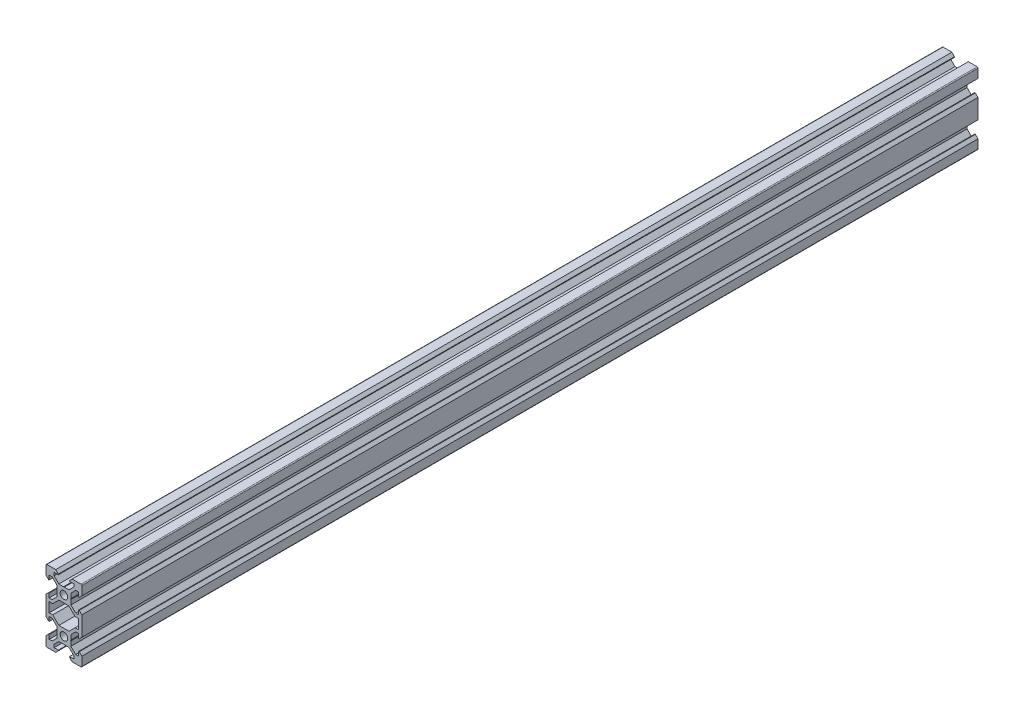
SolidWorks part; units mm, degrees
material "6061-T6 (SS)"
ref_plane "Front Plane" through (0, 0, 0) normal (0, 0, 1) x (1, 0, 0)
ref_plane "Top Plane" through (0, 0, 0) normal (0, 1, 0) x (1, 0, 0)
ref_plane "Right Plane" through (0, 0, 0) normal (1, 0, 0) x (0, 0, -1)
sketch "Sketch1" plane through (0, 0, 0) normal (0, 0, 1) x (1, 0, 0)
  line L0 (0, 0) -> (10, 0) construction
  line L1 (9.5, -20) -> (-9.5, -20)
  line L2 (10, -19.5) -> (10, 19.5)
  line L3 (9.5, 20) -> (-9.5, 20)
  line L4 (-10, -19.5) -> (-10, 19.5)
  line L5 (10, -20) -> (-10, 20) construction
  line L6 (10, 20) -> (-10, -20) construction
  circle A0 centre (0, 10) radius 2.1
  circle A1 centre (0, -10) radius 2.1
  arc A2 (-9.5, -20) -> (-10, -19.5) centre (-9.5, -19.5) cw
  arc A3 (9.5, -20) -> (10, -19.5) centre (9.5, -19.5) ccw
  arc A4 (10, 19.5) -> (9.5, 20) centre (9.5, 19.5) ccw
  arc A5 (-9.5, 20) -> (-10, 19.5) centre (-9.5, 19.5) ccw
  point P0 (0, 0)
  line B0 (0, 10) -> (0, 20) construction
  line B1 (0, 13.69) -> (-0.21, 13.9)
  line B2 (-0.21, 13.9) -> (-2.8393, 13.9)
  line B3 (-2.8393, 13.9) -> (-5.5, 16.5607)
  line B4 (-5.5, 16.5607) -> (-5.5, 18.2)
  line B5 (-5.5, 18.2) -> (-3.125, 18.2)
  line B6 (-3.125, 18.2) -> (-3.125, 18.545)
  line B7 (-3.125, 18.545) -> (-4.58, 20)
  line B8 (-4.58, 20) -> (4.58, 20)
  line B9 (0, 10) -> (-5.9132, 15.9132) construction
  line B10 (3.125, 18.545) -> (4.58, 20)
  line B11 (3.125, 18.2) -> (3.125, 18.545)
  line B12 (5.5, 18.2) -> (3.125, 18.2)
  line B13 (5.5, 16.5607) -> (5.5, 18.2)
  line B14 (2.8393, 13.9) -> (5.5, 16.5607)
  line B15 (0.21, 13.9) -> (2.8393, 13.9)
  line B16 (0, 13.69) -> (0.21, 13.9)
  line B17 (0, 10) -> (-10, 10) construction
  line B18 (-3.69, 10) -> (-3.9, 9.79)
  line B19 (-3.9, 9.79) -> (-3.9, 7.1607)
  line B20 (-3.9, 7.1607) -> (-6.5607, 4.5)
  line B21 (-6.5607, 4.5) -> (-8.2, 4.5)
  line B22 (-8.2, 4.5) -> (-8.2, 6.875)
  line B23 (-8.2, 6.875) -> (-8.545, 6.875)
  line B24 (-8.545, 6.875) -> (-10, 5.42)
  line B25 (-10, 5.42) -> (-10, 14.58)
  line B26 (0, 10) -> (-5.9132, 4.0868) construction
  line B27 (-8.545, 13.125) -> (-10, 14.58)
  line B28 (-8.2, 13.125) -> (-8.545, 13.125)
  line B29 (-8.2, 15.5) -> (-8.2, 13.125)
  line B30 (-6.5607, 15.5) -> (-8.2, 15.5)
  line B31 (-3.9, 12.8393) -> (-6.5607, 15.5)
  line B32 (-3.9, 10.21) -> (-3.9, 12.8393)
  line B33 (-3.69, 10) -> (-3.9, 10.21)
  line B34 (0, -10) -> (-10, -10) construction
  line B35 (-3.69, -10) -> (-3.9, -10.21)
  line B36 (-3.9, -10.21) -> (-3.9, -12.8393)
  line B37 (-3.9, -12.8393) -> (-6.5607, -15.5)
  line B38 (-6.5607, -15.5) -> (-8.2, -15.5)
  line B39 (-8.2, -15.5) -> (-8.2, -13.125)
  line B40 (-8.2, -13.125) -> (-8.545, -13.125)
  line B41 (-8.545, -13.125) -> (-10, -14.58)
  line B42 (-10, -14.58) -> (-10, -5.42)
  line B43 (0, -10) -> (-5.9132, -15.9132) construction
  line B44 (-8.545, -6.875) -> (-10, -5.42)
  line B45 (-8.2, -6.875) -> (-8.545, -6.875)
  line B46 (-8.2, -4.5) -> (-8.2, -6.875)
  line B47 (-6.5607, -4.5) -> (-8.2, -4.5)
  line B48 (-3.9, -7.1607) -> (-6.5607, -4.5)
  line B49 (-3.9, -9.79) -> (-3.9, -7.1607)
  line B50 (-3.69, -10) -> (-3.9, -9.79)
  line B51 (0, -10) -> (0, -20) construction
  line B52 (0, -13.69) -> (0.21, -13.9)
  line B53 (0.21, -13.9) -> (2.8393, -13.9)
  line B54 (2.8393, -13.9) -> (5.5, -16.5607)
  line B55 (5.5, -16.5607) -> (5.5, -18.2)
  line B56 (5.5, -18.2) -> (3.125, -18.2)
  line B57 (3.125, -18.2) -> (3.125, -18.545)
  line B58 (3.125, -18.545) -> (4.58, -20)
  line B59 (4.58, -20) -> (-4.58, -20)
  line B60 (0, -10) -> (5.9132, -15.9132) construction
  line B61 (-3.125, -18.545) -> (-4.58, -20)
  line B62 (-3.125, -18.2) -> (-3.125, -18.545)
  line B63 (-5.5, -18.2) -> (-3.125, -18.2)
  line B64 (-5.5, -16.5607) -> (-5.5, -18.2)
  line B65 (-2.8393, -13.9) -> (-5.5, -16.5607)
  line B66 (-0.21, -13.9) -> (-2.8393, -13.9)
  line B67 (0, -13.69) -> (-0.21, -13.9)
  line B68 (0, -10) -> (10, -10) construction
  line B69 (3.69, -10) -> (3.9, -9.79)
  line B70 (3.9, -9.79) -> (3.9, -7.1607)
  line B71 (3.9, -7.1607) -> (6.5607, -4.5)
  line B72 (6.5607, -4.5) -> (8.2, -4.5)
  line B73 (8.2, -4.5) -> (8.2, -6.875)
  line B74 (8.2, -6.875) -> (8.545, -6.875)
  line B75 (8.545, -6.875) -> (10, -5.42)
  line B76 (10, -5.42) -> (10, -14.58)
  line B77 (0, -10) -> (5.9132, -4.0868) construction
  line B78 (8.545, -13.125) -> (10, -14.58)
  line B79 (8.2, -13.125) -> (8.545, -13.125)
  line B80 (8.2, -15.5) -> (8.2, -13.125)
  line B81 (6.5607, -15.5) -> (8.2, -15.5)
  line B82 (3.9, -12.8393) -> (6.5607, -15.5)
  line B83 (3.9, -10.21) -> (3.9, -12.8393)
  line B84 (3.69, -10) -> (3.9, -10.21)
  line B85 (0, 10) -> (10, 10) construction
  line B86 (3.69, 10) -> (3.9, 10.21)
  line B87 (3.9, 10.21) -> (3.9, 12.8393)
  line B88 (3.9, 12.8393) -> (6.5607, 15.5)
  line B89 (6.5607, 15.5) -> (8.2, 15.5)
  line B90 (8.2, 15.5) -> (8.2, 13.125)
  line B91 (8.2, 13.125) -> (8.545, 13.125)
  line B92 (8.545, 13.125) -> (10, 14.58)
  line B93 (10, 14.58) -> (10, 5.42)
  line B94 (0, 10) -> (5.9132, 15.9132) construction
  line B95 (8.545, 6.875) -> (10, 5.42)
  line B96 (8.2, 6.875) -> (8.545, 6.875)
  line B97 (8.2, 4.5) -> (8.2, 6.875)
  line B98 (6.5607, 4.5) -> (8.2, 4.5)
  line B99 (3.9, 7.1607) -> (6.5607, 4.5)
  line B100 (3.9, 9.79) -> (3.9, 7.1607)
  line B101 (3.69, 10) -> (3.9, 9.79)
  line B102 (-8.2, -2.7) -> (-8.2, 2.7)
  line B103 (-8.2, 2.7) -> (-6.2393, 2.7)
  line B104 (-6.2393, 2.7) -> (-2.8393, 6.1)
  line B105 (-2.8393, 6.1) -> (2.8393, 6.1)
  line B106 (0, 6.1) -> (0, 0) construction
  line B107 (0, 0) -> (-8.2, 0) construction
  line B108 (6.2393, 2.7) -> (2.8393, 6.1)
  line B109 (8.2, 2.7) -> (6.2393, 2.7)
  line B110 (8.2, -2.7) -> (8.2, 2.7)
  line B111 (8.2, -2.7) -> (6.2393, -2.7)
  line B112 (6.2393, -2.7) -> (2.8393, -6.1)
  line B113 (-2.8393, -6.1) -> (2.8393, -6.1)
  line B114 (-6.2393, -2.7) -> (-2.8393, -6.1)
  line B115 (-8.2, -2.7) -> (-6.2393, -2.7)
  line B116 (0, 6.1) -> (0, 10) construction
  line B117 (0, 10) -> (-5.0927, 4.9073) construction
  dimension "D4" = 4.2
  dimension "D5" = 0.5
  dimension "D1" = 20
  dimension "D2" = 40
  dimension "D3" = 20
sketch_block_instance "V Slot 1-4"
sketch_block "V Slot 1" parameters "D1"=10, "D2"=11, "D3"=4.3, "D4"=1.8, "D5"=0.21, "D6"=45, "D7"=9.16, "D8"=1.5, "D9"=6.25
sketch_block_instance "V Slot 1-5"
sketch_block_instance "V Slot 1-6"
sketch_block_instance "V Slot 1-7"
sketch_block_instance "V Slot 1-8"
sketch_block_instance "V Slot 1-9"
sketch_block_instance "Center Cutout 1-1"
sketch_block "Center Cutout 1" parameters "D1"=5.4, "D2"=12.2, "D3"=8.2, "D4"=45, "D5"=10, "D6"=1.5
extrude "Boss-Extrude1" add sketch "Sketch1" along normal blind 500 contours B101 B86 B87 B88 B89 B90 B91 B92 L2 A4 L3 B10 B11 B12 B13 B14 B15 B16 B1 B2 B3 B4 B5 B6 B7 A5 L4 B27 B28 B29 B30 B31 B32 B33 B18 B19 B20 B21 B22 B23 B24 B44 B45 B46 B47 B48 B49 B50 B35
ref_plane "Upper Plane" through (0, 10, 0) normal (0, 1, 0) x (1, 0, 0)
ref_plane "Lower Plane" through (0, -10, 0) normal (0, 1, 0) x (1, 0, 0)
